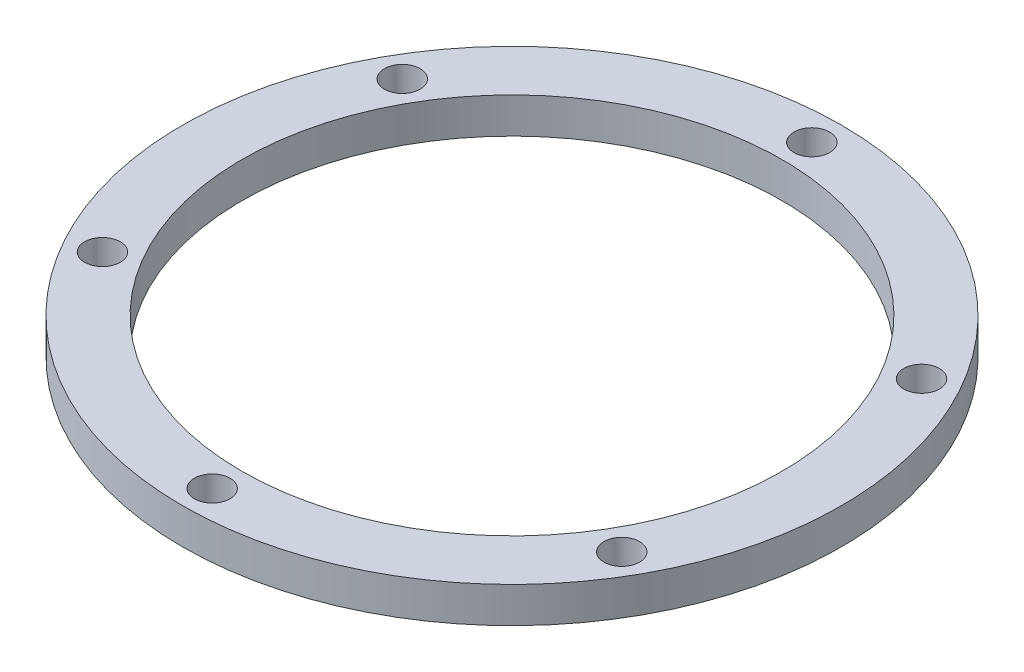
SolidWorks part; units mm, degrees
ref_plane "Front Plane" through (0, 0, 0) normal (0, 0, 1) x (1, 0, 0)
ref_plane "Top Plane" through (0, 0, 0) normal (0, 1, 0) x (1, 0, 0)
ref_plane "Right Plane" through (0, 0, 0) normal (1, 0, 0) x (0, 0, -1)
sketch "Sketch1" plane through (0, 0, 0) normal (0, 1, 0) x (1, 0, 0)
  circle A0 centre (0, 0) radius 25.2 construction
  circle A2 centre (0, 0) radius 27.7
  circle A3 centre (0, 0) radius 22.7
  circle A4 centre (0, 25.2) radius 1.5
  circle A5 centre (21.8238, 12.6) radius 1.5
  circle A6 centre (21.8238, -12.6) radius 1.5
  circle A7 centre (0, -25.2) radius 1.5
  circle A8 centre (-21.8238, -12.6) radius 1.5
  circle A9 centre (-21.8238, 12.6) radius 1.5
  point P10 (0, 0)
  point P21 (0, 0)
  dimension "D1" = 50.4
  dimension "D4" = 3
  dimension "D2" = 2.5
  dimension "D3" = 2.5
  dimension "D5" = 6
extrude "Boss-Extrude1" add sketch "Sketch1" along normal blind 3
